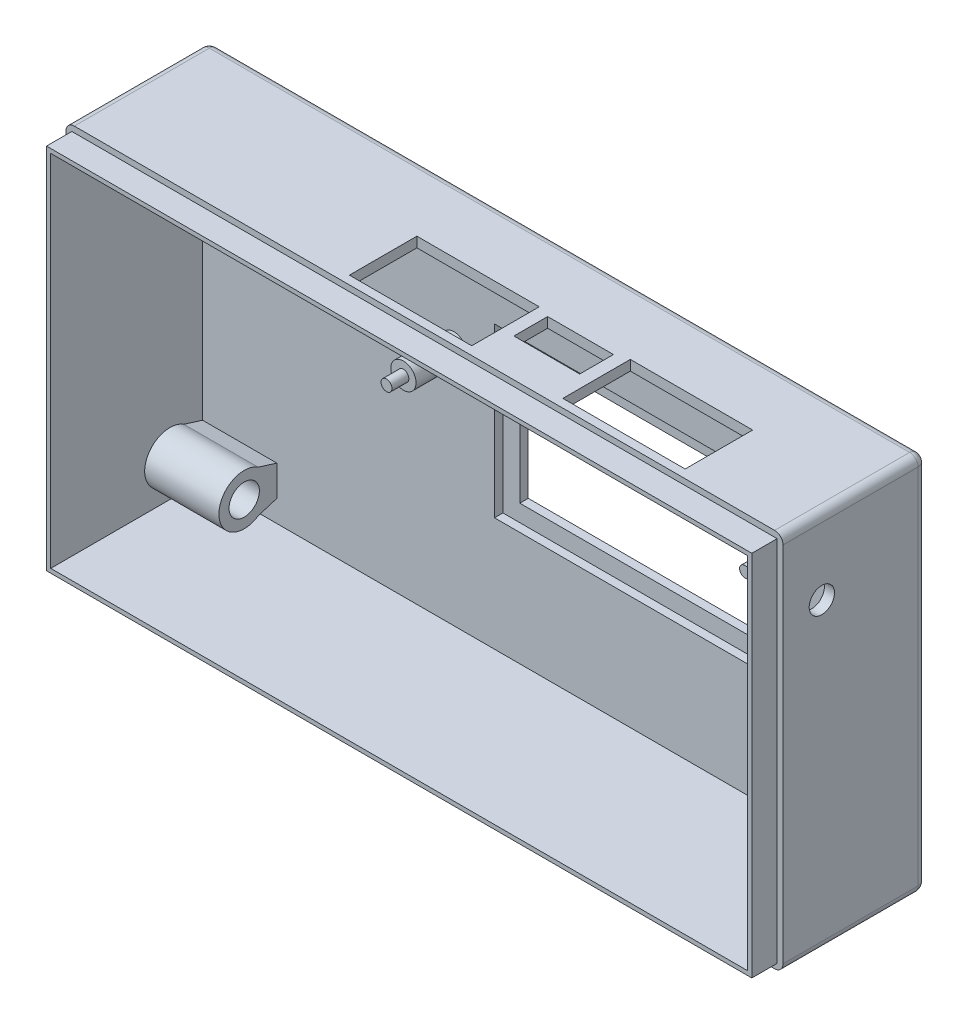
SolidWorks part; units mm, degrees
material "ABS"
ref_plane "Спереди" through (0, 0, 0) normal (0, 0, 1) x (1, 0, 0)
ref_plane "Сверху" through (0, 0, 0) normal (0, 1, 0) x (1, 0, 0)
ref_plane "Справа" through (0, 0, 0) normal (1, 0, 0) x (0, 0, -1)
sketch "Эскиз1" plane through (0, 0, 0) normal (0, 0, 1) x (1, 0, 0)
  line L1 (0, 0) -> (85, 0)
  line L2 (0, 0) -> (0, 45)
  line L3 (0, 45) -> (85, 45)
  line L4 (85, 0) -> (85, 45)
  dimension "D1" = 85
  dimension "D2" = 45
extrude "Бобышка-Вытянуть1" add sketch "Эскиз1" along normal blind 20
sketch "Эскиз2" plane through (0, 0, 20) normal (0, 0, 1) x (1, 0, 0)
  line L0 (42.5, 45) -> (42.5, 0) construction
  line L1 (85, 45) -> (0, 45) construction
  line L2 (0, 0) -> (85, 0) construction
  line L3 (85, 0) -> (85, 45) construction
  line L4 (1.2, 43.8) -> (83.8, 43.8)
  line L5 (1.2, 43.8) -> (1.2, 1.2)
  line L6 (1.2, 1.2) -> (83.8, 1.2)
  line L7 (83.8, 43.8) -> (83.8, 1.2)
  line L8 (1.2, 43.8) -> (83.8, 1.2) construction
  line L9 (1.2, 1.2) -> (83.8, 43.8) construction
  point P6 (42.5, 22.5)
  dimension "D1" = 1.2
  dimension "D2" = 1.2
extrude "Вырез-Вытянуть1" cut sketch "Эскиз2" against normal blind 18
sketch "Эскиз3" plane through (0, 0, 20) normal (0, 0, 1) x (1, 0, 0)
  line L0 (42.5, 45) -> (42.5, 0) construction
  line L1 (85, 45) -> (0, 45) construction
  line L2 (0, 0) -> (85, 0) construction
  line L3 (0, 45) -> (0, 0) construction
  line L4 (0.7, 44.3) -> (84.3, 44.3)
  line L5 (0.7, 44.3) -> (0.7, 0.7)
  line L6 (0.7, 0.7) -> (84.3, 0.7)
  line L7 (84.3, 44.3) -> (84.3, 0.7)
  line L8 (0.7, 44.3) -> (84.3, 0.7) construction
  line L9 (0.7, 0.7) -> (84.3, 44.3) construction
  circle A0 centre (42.5, 22.5) radius 52.5648
  point P6 (42.5, 22.5)
  dimension "D1" = 0.7
  dimension "D2" = 0.7
extrude "Вырез-Вытянуть2" cut sketch "Эскиз3" against normal blind 3
sketch "Эскиз4" plane through (85, 0, 0) normal (-1, 0, 0) x (0, 0, 1)
  line L0 (17, 45) -> (0, 45) construction
  line L1 (0, 45) -> (0, 0) construction
  circle A0 centre (12.4, 36.05) radius 1.5
  dimension "D1" = 8.95
  dimension "D2" = 3
  dimension "D3" = 12.4
extrude "Вырез-Вытянуть3" cut sketch "Эскиз4" along normal blind 10
sketch "Эскиз6" plane through (0, 0, 2) normal (0, 0, 1) x (1, 0, 0)
  line L0 (73.5, 32) -> (31, 32) construction
  line L2 (31, 32) -> (31, 29.89) construction
  circle A0 centre (31, 29.89) radius 1.5
  circle A1 centre (73.5, 32) radius 1.5
  dimension "D2" = 3
  dimension "D3" = 3
  dimension "D5" = 31
  dimension "D1" = 42.5
  dimension "D4" = 2.11
  dimension "D6" = 32
extrude "Бобышка-Вытянуть2" add sketch "Эскиз6" along normal blind 6
sketch "Эскиз7" plane through (0, 0, 8) normal (0, 0, 1) x (1, 0, 0)
  circle A0 centre (31, 29.89) radius 0.65
  circle A1 centre (73.5, 32) radius 0.65
  dimension "D1" = 1.3
  dimension "D2" = 1.3
extrude "Бобышка-Вытянуть3" add sketch "Эскиз7" along normal blind 2
sketch "Эскиз5" plane through (0, 0, 0) normal (0, 0, -1) x (-1, 0, 0)
  line L1 (-65.8, 32.59) -> (-37.8, 32.59)
  line L2 (-65.8, 32.59) -> (-65.8, 16.69)
  line L3 (-65.8, 16.69) -> (-37.8, 16.69)
  line L4 (-37.8, 32.59) -> (-37.8, 16.69)
  circle A0 centre (-31, 29.89) radius 1.5 construction
  dimension "D3" = 6.8
  dimension "D4" = 2.7
  dimension "D1" = 28
  dimension "D2" = 15.9
extrude "Вырез-Вытянуть4" cut sketch "Эскиз5" against normal through all
sketch "Эскиз9" plane through (0, 0, 2) normal (0, 0, 1) x (1, 0, 0)
  line L0 (37.8, 32.59) -> (65.8, 16.69) construction
  line L1 (65.8, 32.59) -> (37.8, 16.69) construction
  line L2 (65.8, 32.59) -> (37.8, 32.59) construction
  line L3 (35.8, 14.69) -> (67.8, 14.69)
  line L4 (35.8, 14.69) -> (35.8, 34.59)
  line L5 (35.8, 34.59) -> (67.8, 34.59)
  line L6 (67.8, 14.69) -> (67.8, 34.59)
  line L7 (35.8, 14.69) -> (67.8, 34.59) construction
  line L8 (35.8, 34.59) -> (67.8, 14.69) construction
  line L9 (65.8, 16.69) -> (65.8, 32.59) construction
  point P8 (51.8, 24.64)
  dimension "D1" = 2
  dimension "D2" = 2
extrude "Вырез-Вытянуть5" cut sketch "Эскиз9" against normal blind 1
sketch "Эскиз10" plane through (0, 45, 0) normal (0, -1, 0) x (1, 0, 0)
  line L0 (47.1, 8) -> (57.9, 8) construction
  line L1 (32.6, 8) -> (47.1, 8)
  line L2 (32.6, 8) -> (32.6, 16)
  line L3 (32.6, 16) -> (47.1, 16)
  line L4 (47.1, 8) -> (47.1, 16)
  line L5 (57.9, 8) -> (72.4, 8)
  line L6 (57.9, 8) -> (57.9, 16)
  line L7 (57.9, 16) -> (72.4, 16)
  line L8 (72.4, 8) -> (72.4, 16)
  line L9 (47.1, 16) -> (57.9, 16) construction
  line L10 (52.5, 8.5) -> (52.5, 8) construction
  line L11 (48.6, 12.5) -> (56.4, 12.5)
  line L12 (48.6, 12.5) -> (48.6, 8.5)
  line L13 (48.6, 8.5) -> (56.4, 8.5)
  line L14 (56.4, 12.5) -> (56.4, 8.5)
  line L15 (0, 17) -> (0, 0) construction
  line L16 (0, 0) -> (85, 0) construction
  dimension "D1" = 14.5
  dimension "D2" = 14.5
  dimension "D3" = 8
  dimension "D4" = 7.8
  dimension "D5" = 4
  dimension "D6" = 10.8
  dimension "D7" = 1
  dimension "D8" = 52.5
  dimension "D9" = 8
extrude "Вырез-Вытянуть6" cut sketch "Эскиз10" along normal blind 10
fillet "Скругление1" radius 1 8 edges at (0, 22.5, 0) (85, 22.5, 0) (42.5, 0, 0) (42.5, 45, 0) (0, 0, 8.5) (0, 45, 8.5) (85, 45, 8.5) (85, 0, 8.5)
sketch "Эскиз11" plane through (0, 0, 0) normal (-1, 0, 0) x (0, 0, 1)
  line L0 (0, 5.5942) -> (5.8671, 5.5942) construction
  line L1 (0, 1) -> (0, 44) construction
  line L2 (1, 4.0942) -> (1, 7.0942)
  line L3 (1, 44) -> (1, 1) construction
  line L4 (1, 7.0942) -> (4.2088, 8.0942)
  line L5 (1, 4.0942) -> (4.2088, 3.0942)
  circle A0 centre (5.8671, 5.5942) radius 1.8
  circle A1 centre (5.8671, 5.5942) radius 3
  point P11 (6.6367, 5.7759)
  point P12 (4.2088, 7.538)
  point P13 (1, 7.0942)
  point P15 (1, 5.5942)
  dimension "D1" = 6
  dimension "D2" = 3.6
  dimension "D3" = 3
  dimension "D4" = 5
extrude "Бобышка-Вытянуть4" add sketch "Эскиз11" against normal blind 10
sketch "Эскиз12" plane through (10, 0, 0) normal (1, 0, 0) x (0, 0, -1)
  circle A0 centre (-5.8671, 5.5942) radius 1.8
  dimension "D1" = 3.6
extrude "Вырез-Вытянуть7" cut sketch "Эскиз12" against normal through all
sketch "Эскиз13" plane through (0, 0, 2) normal (0, 0, 1) x (1, 0, 0)
  circle A0 centre (7, 37.89) radius 2.425
  circle A1 centre (31, 29.89) radius 0.65 construction
  circle A2 centre (31, 29.89) radius 0.65 construction
  dimension "D1" = 4.85
  dimension "D2" = 8
  dimension "D3" = 24
extrude "Вырез-Вытянуть8" cut sketch "Эскиз13" against normal through all
